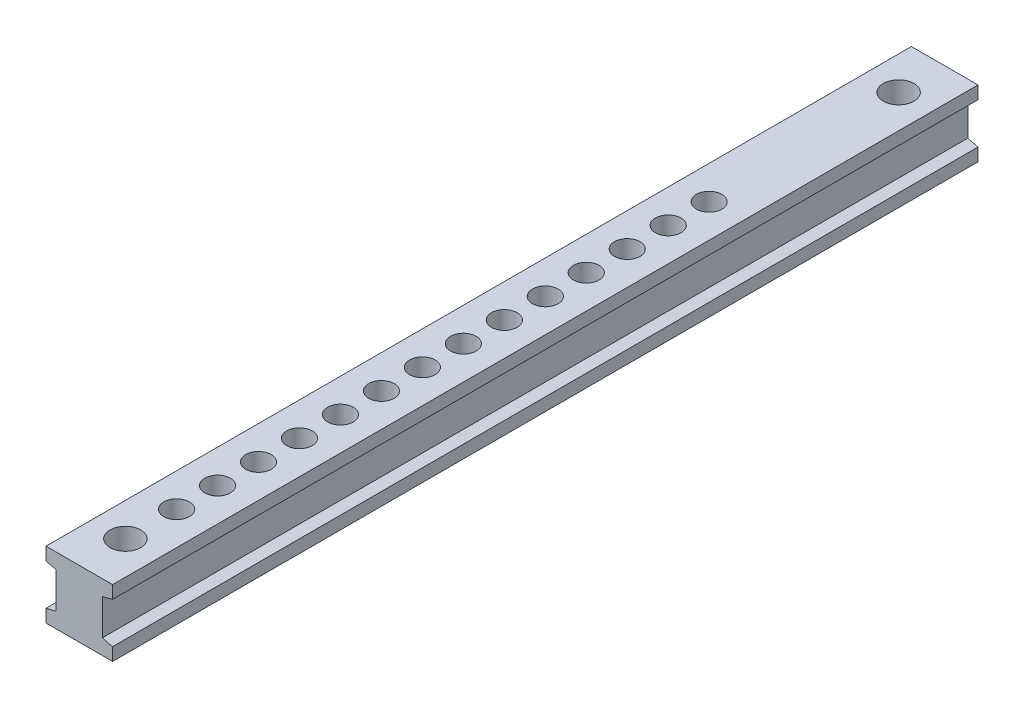
SolidWorks part; units mm, degrees
ref_plane "Front Plane" through (0, 0, 0) normal (0, 0, 1) x (1, 0, 0)
ref_plane "Top Plane" through (0, 0, 0) normal (0, 1, 0) x (1, 0, 0)
ref_plane "Right Plane" through (0, 0, 0) normal (1, 0, 0) x (0, 0, -1)
sketch "Sketch1" plane through (0, 0, 0) normal (0, 0, 1) x (1, 0, 0)
  line L0 (6.5, 4) -> (4.5, 3.5)
  line L1 (-6.5, 6.5) -> (6.5, 6.5)
  line L2 (-6.5, 6.5) -> (-6.5, -6.5)
  line L3 (-6.5, -6.5) -> (6.5, -6.5)
  line L4 (6.5, 6.5) -> (6.5, -6.5)
  line L5 (-6.5, 6.5) -> (6.5, -6.5) construction
  line L6 (-6.5, -6.5) -> (6.5, 6.5) construction
  line L7 (4.5, 3.5) -> (4.5, -3.5)
  line L8 (4.5, -3.5) -> (6.5, -4)
  line L9 (-4.5, 0) -> (4.5, 0) construction
  line L10 (0, -6.5) -> (0, 6.5) construction
  line L11 (6.5, -6.5) -> (-6.5, 6.5) construction
  line L12 (6.5, 6.5) -> (-6.5, -6.5) construction
  line L13 (-4.5, -3.5) -> (-6.5, -4)
  line L14 (-4.5, 3.5) -> (-4.5, -3.5)
  line L15 (-6.5, 6.5) -> (-6.5, -6.5)
  line L16 (-6.5, 4) -> (-4.5, 3.5)
  point P0 (0, 0)
  point P13 (0, 0)
  dimension "D1" = 13
  dimension "D2" = 13
  dimension "D3" = 7
  dimension "D4" = 2
  dimension "D5" = 8
extrude "Boss-Extrude1" add sketch "Sketch1" along normal mid plane 169 contours L2 L16 L14 L13 L3 L4 L8 L7 L0 L1
sketch "Sketch2" plane through (0, 0, 0) normal (0, 1, 0) x (1, 0, 0)
  line L0 (0, 84.5) -> (0, -84.5) construction
  line L1 (-6.5, 84.5) -> (6.5, 84.5) construction
  line L2 (-6.5, -84.5) -> (6.5, -84.5) construction
  line L3 (0, -65.5) -> (0, -57.5) construction
  circle A0 centre (0, 75.5) radius 3
  circle A1 centre (0, -75.5) radius 3
  circle A2 centre (0, -65.5) radius 2.5
  circle A3 centre (0, -57.5) radius 2.5
  circle A4 centre (0, -49.5) radius 2.5
  circle A5 centre (0, -41.5) radius 2.5
  circle A6 centre (0, -33.5) radius 2.5
  circle A7 centre (0, -25.5) radius 2.5
  circle A8 centre (0, -17.5) radius 2.5
  circle A9 centre (0, -9.5) radius 2.5
  circle A10 centre (0, -1.5) radius 2.5
  circle A11 centre (0, 6.5) radius 2.5
  circle A12 centre (0, 14.5) radius 2.5
  circle A13 centre (0, 22.5) radius 2.5
  circle A14 centre (0, 30.5) radius 2.5
  circle A15 centre (0, 38.5) radius 2.5
  dimension "D2" = 6
  dimension "D4" = 5
  dimension "D1" = 9
  dimension "D3" = 9
  dimension "D5" = 19
  dimension "D7" = 8
  dimension "D6" = 14
extrude "Cut-Extrude1" cut sketch "Sketch2" against normal through all both and the other way through all
equation "\"D3@Sketch2\"=\"D1@Sketch2\""
